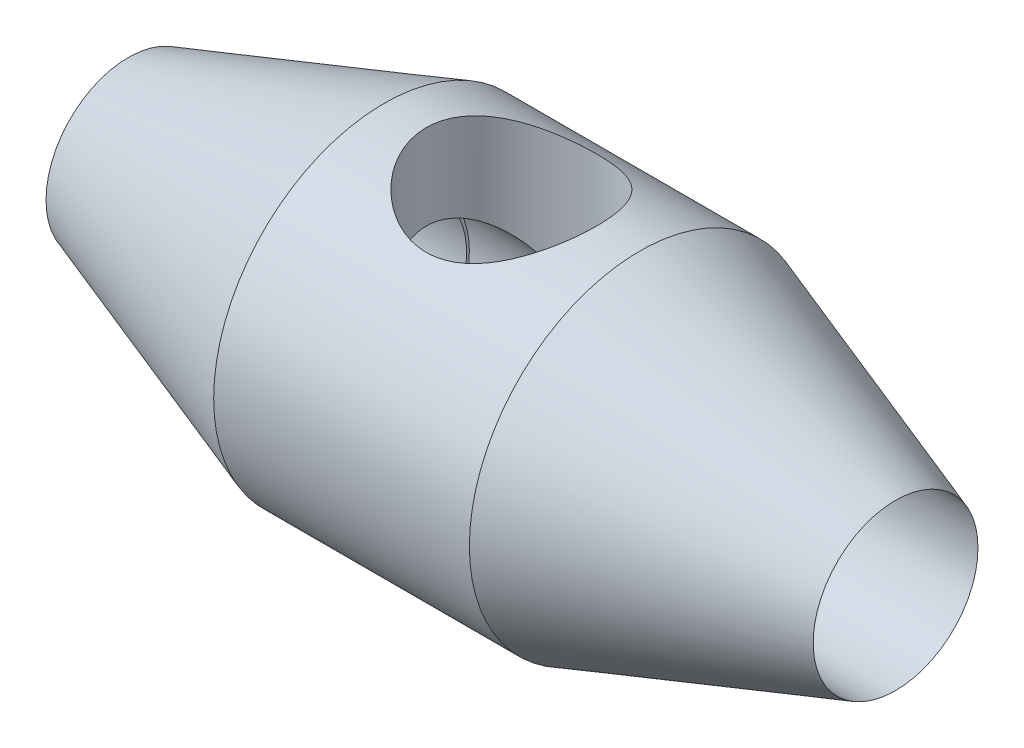
SolidWorks part; units mm, degrees
ref_plane "Front Plane" through (0, 0, 0) normal (0, 0, 1) x (1, 0, 0)
ref_plane "Top Plane" through (0, 0, 0) normal (0, 1, 0) x (1, 0, 0)
ref_plane "Right Plane" through (0, 0, 0) normal (1, 0, 0) x (0, 0, -1)
sketch "Sketch1" plane through (0, 0, 0) normal (1, 0, 0) x (0, 0, -1)
  circle A0 centre (0, 0) radius 50.8
  circle A1 centre (0, 0) radius 25.4
  dimension "D1" = 101.6
  dimension "D2" = 50.8
extrude "Boss-Extrude1" add sketch "Sketch1" along normal blind 76.2
sketch "Sketch2" plane through (0, 0, 0) normal (-1, 0, 0) x (0, 0, 1)
  circle A1 centre (0, 0) radius 50.8
  circle A2 centre (0, 0) radius 50.8
  dimension "D1" = 0
extrude "Boss-Extrude2" add sketch "Sketch2" along normal blind 76.2 draft 19
sketch "Sketch3" plane through (76.2, 0, 0) normal (1, 0, 0) x (0, 0, -1)
  circle A1 centre (0, 0) radius 50.8
  circle A2 centre (0, 0) radius 50.8
  dimension "D1" = 0
extrude "Boss-Extrude3" add sketch "Sketch3" along normal blind 76.2 draft 19
sketch "Sketch4" plane through (-76.2, 0, 0) normal (-1, 0, 0) x (0, 0, 1)
  circle A1 centre (0, 0) radius 24.5622
  circle A2 centre (0, 0) radius 24.5622
  dimension "D1" = 0
extrude "Cut-Extrude1" cut sketch "Sketch4" against normal blind 270.002
ref_plane "Plane1" through (0, 254, 0) normal (0, 1, 0) x (1, 0, 0)
sketch "Sketch5" plane through (0, 254, 0) normal (0, 1, 0) x (1, 0, 0)
  line L0 (-87.8002, 0) -> (163.6574, 0) construction
  circle A0 centre (37.9286, 0) radius 25.4
  dimension "D1" = 50.8
extrude "Cut-Extrude2" cut sketch "Sketch5" against normal blind 295.402
